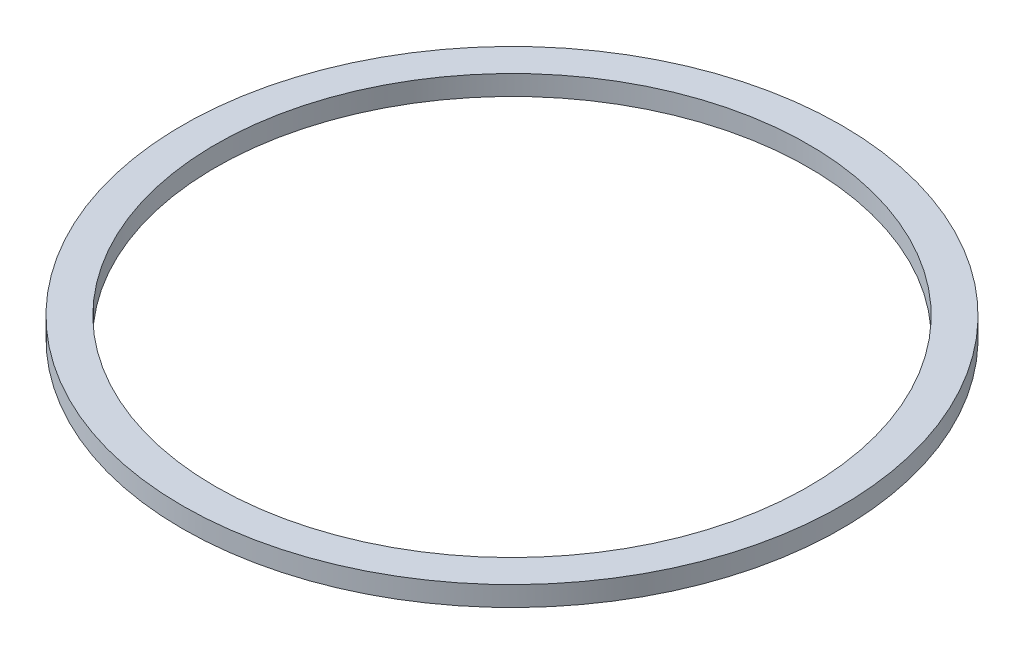
SolidWorks part; units mm, degrees
ref_plane "Front Plane" through (0, 0, 0) normal (0, 0, 1) x (1, 0, 0)
ref_plane "Top Plane" through (0, 0, 0) normal (0, 1, 0) x (1, 0, 0)
ref_plane "Right Plane" through (0, 0, 0) normal (1, 0, 0) x (0, 0, -1)
sketch "Sketch1" plane through (0, 0, 0) normal (0, 1, 0) x (1, 0, 0)
  circle A0 centre (0, 0) radius 8945
  circle A1 centre (0, 0) radius 9945
  dimension "17" = 17890
  dimension "D2" = 19890
extrude "Boss-Extrude1" add sketch "Sketch1" along normal blind 600
